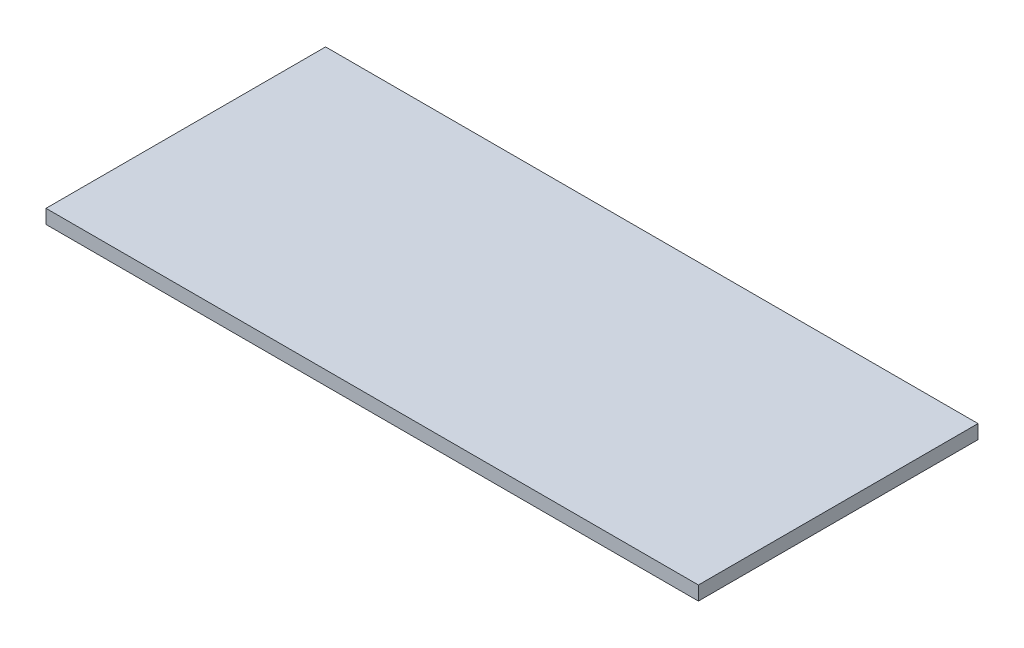
SolidWorks part; units mm, degrees
ref_plane "Alzado" through (0, 0, 0) normal (0, 0, 1) x (1, 0, 0)
ref_plane "Planta" through (0, 0, 0) normal (0, 1, 0) x (1, 0, 0)
ref_plane "Vista lateral" through (0, 0, 0) normal (1, 0, 0) x (0, 0, -1)
sketch "Croquis1" plane through (0, 0, 0) normal (0, 1, 0) x (1, 0, 0)
  line L1 (-350, -150) -> (350, -150)
  line L2 (-350, -150) -> (-350, 150)
  line L3 (-350, 150) -> (350, 150)
  line L4 (350, -150) -> (350, 150)
  line L5 (-350, -150) -> (350, 150) construction
  line L6 (-350, 150) -> (350, -150) construction
  point P0 (0, 0)
  dimension "D1" = 700
  dimension "D2" = 300
extrude "Saliente-Extruir1" add sketch "Croquis1" along normal blind 15
